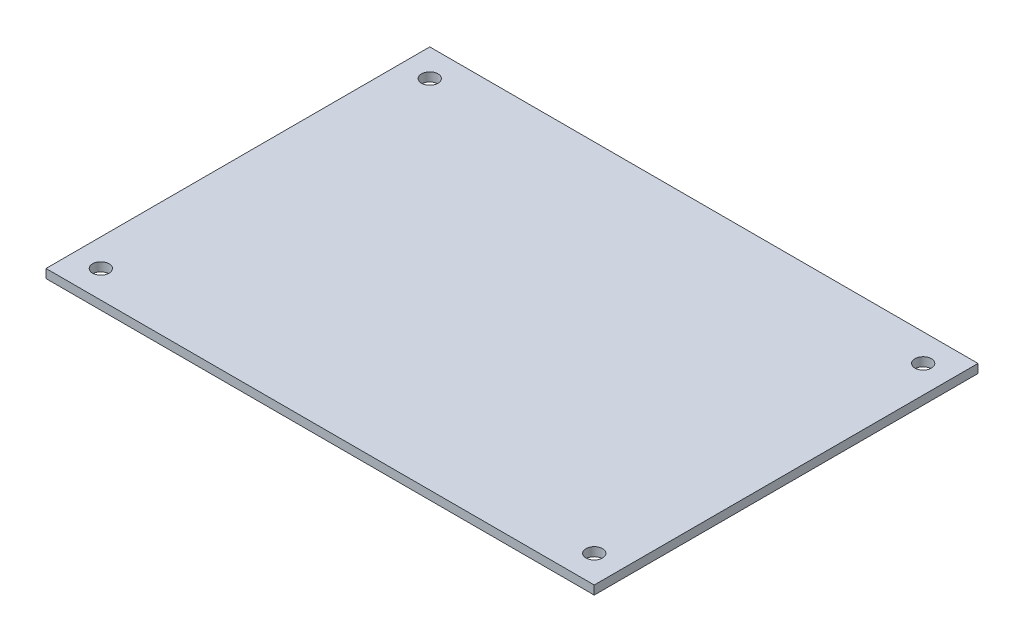
SolidWorks part; units mm, degrees
other "标注1"
sketch "草图3" plane through (-100, 1.6, -70) normal (0, 1, 0) x (1, 0, 0)
ref_plane "前视基准面" through (0, 0, 0) normal (0, 0, 1) x (1, 0, 0)
ref_plane "上视基准面" through (0, 0, 0) normal (0, 1, 0) x (1, 0, 0)
ref_plane "右视基准面" through (0, 0, 0) normal (1, 0, 0) x (0, 0, -1)
other "Configuration Table"
sketch "草图1" plane through (0, 0, 0) normal (0, 1, 0) x (1, 0, 0)
  line L0 (0, 0) -> (-100, 0)
  line L4 (0, 0) -> (0, 70)
  line L7 (-100, 0) -> (-100, 70)
  line L10 (-100, 70) -> (0, 70)
  point P2 (-56, 1.0872)
  point P4 (0.0294, 0)
  dimension "D1" = 70
  dimension "D2" = 100
extrude "凸台-拉伸1" add sketch "草图1" along normal blind 1.6
sketch "草图2" plane through (0, 1.6, 0) normal (0, 1, 0) x (1, 0, 0)
  line L0 (-50, 70) -> (-50, 0) construction
  line L1 (0, 70) -> (-100, 70) construction
  line L2 (-100, 0) -> (0, 0) construction
  line L3 (-100, 35) -> (6.3005, 35) construction
  line L4 (-100, 70) -> (-100, 0) construction
  circle A0 centre (-95, 65) radius 1.5
  circle A1 centre (-95, 5) radius 1.5
  circle A2 centre (-5, 5) radius 1.5
  circle A3 centre (-5, 65) radius 1.5
  dimension "D1" = 3
  dimension "D2" = 5
  dimension "D3" = 5
extrude "切除-拉伸1" cut sketch "草图2" against normal through all
